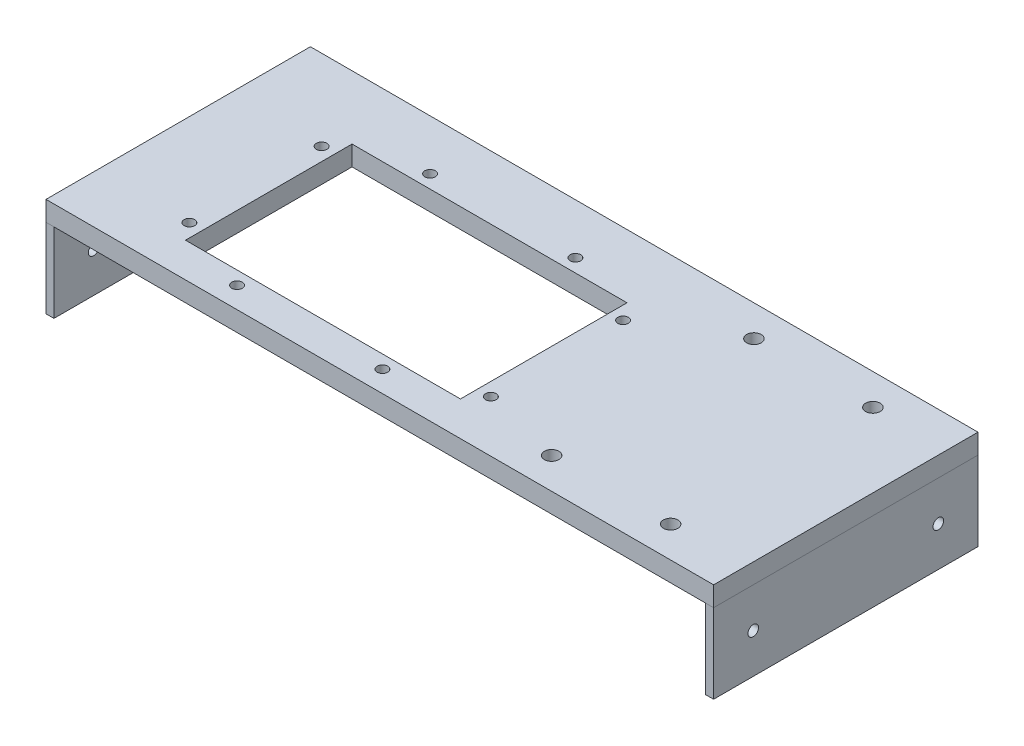
SolidWorks part; units mm, degrees
material "Plain Carbon Steel"
ref_plane "Front Plane" through (0, 0, 0) normal (0, 0, 1) x (1, 0, 0)
ref_plane "Top Plane" through (0, 0, 0) normal (0, 1, 0) x (1, 0, 0)
ref_plane "Right Plane" through (0, 0, 0) normal (1, 0, 0) x (0, 0, -1)
sketch "Sketch1" plane through (0, 0, 0) normal (0, 1, 0) x (1, 0, 0)
  line L0 (0, 0) -> (-252.5, 0) construction
  line L1 (0, 0) -> (0, 100) construction
  line L8 (252.5, 100) -> (-252.5, 100)
  line L9 (-252.5, 100) -> (-252.5, -100)
  line L10 (-252.5, -100) -> (252.5, -100)
  line L11 (252.5, -100) -> (252.5, 100)
  circle A4 centre (227.5, -75) radius 5 construction
  circle A5 centre (227.5, 75) radius 5 construction
  circle A6 centre (-227.5, -75) radius 5 construction
  circle A7 centre (-227.5, 75) radius 5 construction
  circle A16 centre (106.5, -76.5) radius 5.5 construction
  circle A17 centre (196.5, -76.5) radius 5.5 construction
  circle A18 centre (196.5, 76.5) radius 5.5 construction
  circle A19 centre (106.5, 76.5) radius 5.5 construction
  circle A20 centre (106.5, -76.5) radius 5.5
  circle A21 centre (196.5, -76.5) radius 5.5
  circle A22 centre (196.5, 76.5) radius 5.5
  circle A23 centre (106.5, 76.5) radius 5.5
  circle A32 centre (45, -61) radius 4
  circle A33 centre (-14, -84) radius 4
  circle A34 centre (-124, -84) radius 4
  circle A35 centre (-183, -61) radius 4
  circle A36 centre (-183, 39) radius 4
  circle A37 centre (-124, 62) radius 4
  circle A38 centre (45, 39) radius 4
  circle A39 centre (-14, 62) radius 4
  dimension "D4" = 25
  dimension "D5" = 10
  dimension "D1" = 505
  dimension "D2" = 200
  dimension "D3" = 25
extrude "Boss-Extrude1" add sketch "Sketch1" against normal blind 15
sketch "Sketch2" plane through (0, -15, 0) normal (0, -1, 0) x (1, 0, 0)
  line L1 (-173, 74) -> (35, 74)
  line L2 (-173, 74) -> (-173, -52)
  line L3 (-173, -52) -> (35, -52)
  line L4 (35, 74) -> (35, -52)
extrude "Shredder Opening" cut sketch "Sketch2" against normal through all
sketch "Sketch3" plane through (0, 0, 0) normal (0, 1, 0) x (1, 0, 0)
  line L0 (252.5, 100) -> (-252.5, 100) construction
  line L1 (200, 100) -> (30, 100)
  line L2 (200, 100) -> (200, 176.5)
  line L3 (200, 176.5) -> (30, 176.5)
  line L4 (30, 100) -> (30, 176.5)
  line L8 (115, 176.5) -> (115, 267.7218) construction
  circle A1 centre (175, 151.5) radius 5
  circle A2 centre (55, 151.5) radius 5
extrude "Legs add on" [suppressed] add sketch "Sketch3" against normal through all
sketch "Sketch4" plane through (0, 0, 100) normal (0, 0, 1) x (1, 0, 0)
  line L0 (0, -15) -> (0, -97.7912) construction
  line L1 (-252.5, -15) -> (-246.5, -15)
  line L2 (-252.5, -15) -> (-252.5, -75)
  line L3 (-252.5, -75) -> (-246.5, -75)
  line L4 (-246.5, -15) -> (-246.5, -75)
  line L5 (-252.5, -15) -> (252.5, -15) construction
  line L6 (246.5, -15) -> (246.5, -75)
  line L7 (252.5, -75) -> (246.5, -75)
  line L8 (252.5, -15) -> (252.5, -75)
  line L9 (252.5, -15) -> (246.5, -15)
  dimension "D1" = 60
  dimension "D2" = 6
extrude "Boss-Extrude2" add sketch "Sketch4" against normal through all separate body
sketch "Sketch5" plane through (-252.5, 0, 0) normal (-1, 0, 0) x (0, 0, 1)
  line L0 (0, -75) -> (0, -118.3722) construction
  line L1 (-100, -75) -> (100, -75) construction
  line L2 (100, -15) -> (100, -75) construction
  circle A0 centre (70, -45) radius 4
  circle A1 centre (-70, -45) radius 4
  point P11 (100, -45)
  dimension "D1" = 8
  dimension "D2" = 26
extrude "Cut-Extrude1" cut sketch "Sketch5" against normal through all
